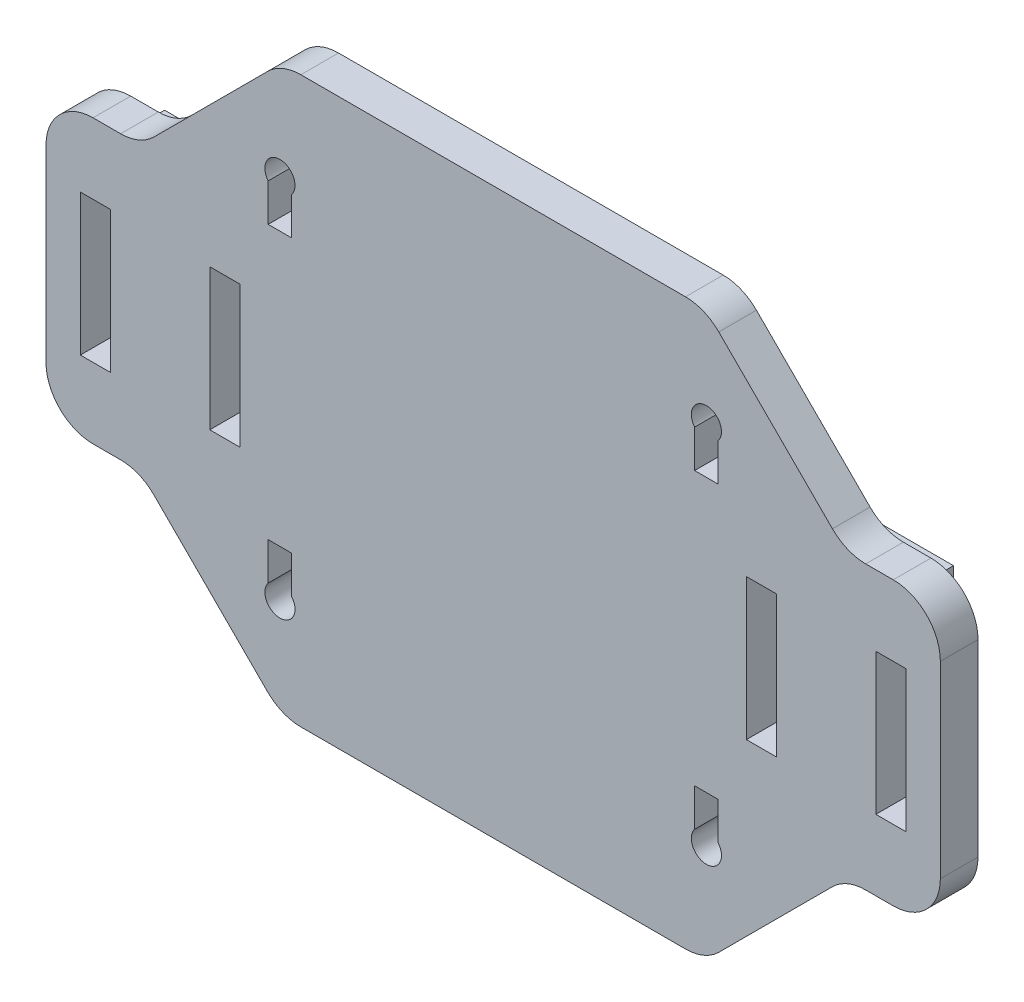
SolidWorks part; units mm, degrees
ref_plane "前视基准面" through (0, 0, 0) normal (0, 0, 1) x (1, 0, 0)
ref_plane "上视基准面" through (0, 0, 0) normal (0, 1, 0) x (1, 0, 0)
ref_plane "右视基准面" through (0, 0, 0) normal (1, 0, 0) x (0, 0, -1)
sketch "草图1" plane through (0, 0, 0) normal (0, 0, 1) x (1, 0, 0)
  line L1 (0, 0) -> (75, 0)
  line L2 (0, 0) -> (0, 60)
  line L3 (0, 60) -> (75, 60)
  line L4 (75, 0) -> (75, 60)
  dimension "D1" = 75
  dimension "D2" = 60
extrude "凸台-拉伸1" add sketch "草图1" along normal blind 4
sketch "草图2" plane through (0, 0, 4) normal (0, 0, 1) x (1, 0, 0)
  line L0 (75, 0) -> (75, 60) construction
  line L5 (64.4, 37.5) -> (67.6, 37.5)
  line L6 (64.4, 37.5) -> (64.4, 22.5)
  line L7 (64.4, 22.5) -> (67.6, 22.5)
  line L8 (67.6, 37.5) -> (67.6, 22.5)
  line L9 (75, 60) -> (0, 60) construction
  line L10 (37.5, 60) -> (37.5, 4.9839) construction
  line L19 (10.6, 37.5) -> (7.4, 37.5)
  line L20 (7.4, 37.5) -> (7.4, 22.5)
  line L21 (10.6, 22.5) -> (7.4, 22.5)
  line L22 (10.6, 37.5) -> (10.6, 22.5)
  point P8 (66, 37.5)
  point P11 (67.6, 30)
  point P16 (75, 30)
  dimension "D1" = 0
  dimension "D2" = 3.2
  dimension "D3" = 9
  dimension "D5" = 15
extrude "切除-拉伸1" cut sketch "草图2" against normal through all
sketch "草图3" plane through (0, 0, 4) normal (0, 0, 1) x (1, 0, 0)
  line L2 (58.9, 48.5) -> (58.9, 44.5)
  line L3 (58.9, 44.5) -> (61.4, 44.5)
  line L4 (61.4, 48.5) -> (61.4, 44.5)
  line L5 (58.9, 15.5) -> (61.4, 15.5)
  line L6 (58.9, 15.5) -> (58.9, 11.5)
  line L8 (61.4, 15.5) -> (61.4, 11.5)
  line L11 (37.5, 60) -> (37.5, 33.4839) construction
  line L12 (75, 60) -> (0, 60) construction
  line L21 (16.1, 15.5) -> (16.1, 11.5)
  line L22 (13.6, 15.5) -> (13.6, 11.5)
  line L23 (16.1, 15.5) -> (13.6, 15.5)
  line L24 (13.6, 48.5) -> (13.6, 44.5)
  line L25 (16.1, 44.5) -> (13.6, 44.5)
  line L26 (16.1, 48.5) -> (16.1, 44.5)
  line L27 (64.4, 37.5) -> (64.4, 22.5) construction
  line L28 (67.6, 37.5) -> (64.4, 37.5) construction
  line L29 (64.4, 22.5) -> (67.6, 22.5) construction
  arc A4 (16.1, 11.5) -> (13.6, 11.5) centre (14.85, 10.5013) cw
  arc A5 (13.6, 48.5) -> (16.1, 48.5) centre (14.85, 49.4987) cw
  arc A6 (61.4, 48.5) -> (58.9, 48.5) centre (60.15, 49.4987) ccw
  arc A7 (58.9, 11.5) -> (61.4, 11.5) centre (60.15, 10.5013) ccw
  dimension "D9" = 2.5
  dimension "D10" = 4
  dimension "D11" = 1.25
  dimension "D12" = 1.25
  dimension "D1" = 4
  dimension "D2" = 4
  dimension "D3" = 4
  dimension "D4" = 2.5
  dimension "D5" = 3
  dimension "D6" = 7
  dimension "D7" = 3
  dimension "D8" = 7
extrude "切除-拉伸2" cut sketch "草图3" against normal through all
chamfer "倒角1" distance 15 angle 45 4 edges at (0, 60, 2) (75, 0, 2) (0, 0, 2) (75, 60, 2)
sketch "草图7" plane through (0, 0, 4) normal (0, 0, 1) x (1, 0, 0)
  line L1 (0, 45) -> (-10, 45)
  line L2 (0, 45) -> (0, 15)
  line L3 (0, 15) -> (-10, 15)
  line L4 (-10, 45) -> (-10, 15)
  line L5 (75, 45) -> (85, 45)
  line L6 (75, 45) -> (75, 15)
  line L7 (75, 15) -> (85, 15)
  line L8 (85, 45) -> (85, 15)
  dimension "D1" = 10
  dimension "D2" = 10
extrude "凸台-拉伸3" add sketch "草图7" against normal up to surface (4 mm away) up to face at (14.85, 47.1497, 0)
sketch "草图8" plane through (0, 0, 4) normal (0, 0, 1) x (1, 0, 0)
  line L0 (67.6, 37.5) -> (64.4, 37.5) construction
  line L1 (81.35, 22.5) -> (78.15, 22.5)
  line L2 (81.35, 22.5) -> (81.35, 37.5)
  line L3 (81.35, 37.5) -> (78.15, 37.5)
  line L4 (78.15, 22.5) -> (78.15, 37.5)
  line L5 (37.5, 60) -> (37.5, 41.1196) construction
  line L6 (60, 60) -> (15, 60) construction
  line L7 (-6.35, 37.5) -> (-3.15, 37.5)
  line L8 (-3.15, 22.5) -> (-3.15, 37.5)
  line L9 (-6.35, 22.5) -> (-3.15, 22.5)
  line L10 (-6.35, 22.5) -> (-6.35, 37.5)
  line L11 (64.4, 22.5) -> (67.6, 22.5) construction
  point P6 (66, 37.5)
  point P7 (79.75, 37.5)
  dimension "D1" = 0
  dimension "D2" = 13.75
  dimension "D3" = 3.2
  dimension "D4" = 0
extrude "切除-拉伸5" cut sketch "草图8" against normal through all
fillet "圆角1" radius 5 12 edges at (15, 0, 2) (60, 0, 2) (75, 15, 2) (85, 15, 2) (85, 45, 2) (75, 45, 2) (60, 60, 2) (15, 60, 2) (0, 45, 2) (0, 15, 2) (-10, 15, 2) (-10, 45, 2)
sketch "草图5" plane through (0, 0, 0) normal (0, 0, -1) x (-1, 0, 0)
  line L1 (-79.4, 42.5) -> (4.4, 42.5)
  line L2 (-79.4, 42.5) -> (-79.4, 38.5)
  line L3 (-79.4, 38.5) -> (-39.5, 38.5)
  line L7 (-37.5, 42.5) -> (-37.5, 17.5)
  line L9 (-79.4, 17.5) -> (-79.4, 21.5)
  line L10 (-79.4, 17.5) -> (4.4, 17.5)
  line L12 (-79.4, 21.5) -> (-39.5, 21.5)
  line L15 (-39.5, 38.5) -> (-39.5, 21.5)
  line L18 (-64.4, 37.5) -> (-64.4, 22.5) construction
  line L19 (-64.4, 22.5) -> (-67.6, 22.5) construction
  line L20 (-67.6, 37.5) -> (-64.4, 37.5) construction
  line L21 (-57.9289, 60) -> (-17.0711, 60) construction
  line L22 (4.4, 42.5) -> (4.4, 38.5)
  line L23 (4.4, 38.5) -> (-35.5, 38.5)
  line L24 (-35.5, 38.5) -> (-35.5, 21.5)
  line L25 (4.4, 21.5) -> (-35.5, 21.5)
  line L26 (4.4, 17.5) -> (4.4, 21.5)
  point P7 (-37.5, 60)
  dimension "D1" = 4
  dimension "D2" = 15
  dimension "D3" = 1
  dimension "D4" = 15
  dimension "D5" = 2
  dimension "D6" = 4
  dimension "D7" = 1
  dimension "D8" = 0
extrude "凸台-拉伸2" add sketch "草图5" along normal blind 3 contours L3 L15 L12 L9 L10 L7 L1 L2 | L10 L26 L25 L24 L23 L22 L1 L7
